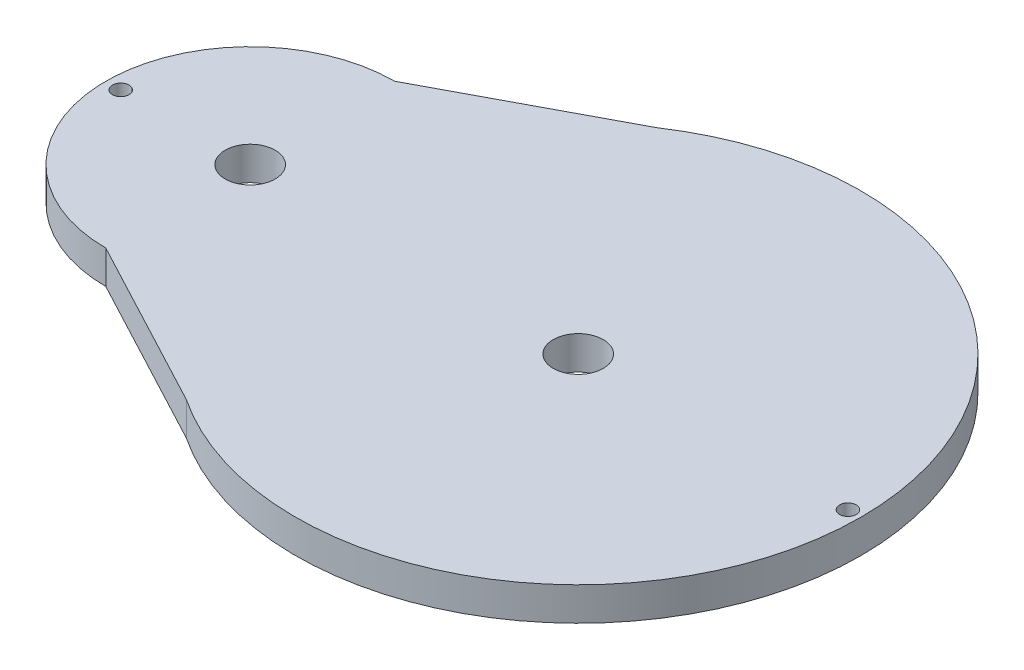
SolidWorks part; units mm, degrees
ref_plane "Front Plane" through (0, 0, 0) normal (0, 0, 1) x (1, 0, 0)
ref_plane "Top Plane" through (0, 0, 0) normal (0, 1, 0) x (1, 0, 0)
ref_plane "Right Plane" through (0, 0, 0) normal (1, 0, 0) x (0, 0, -1)
sketch "Sketch1" plane through (0, 0, 0) normal (0, 1, 0) x (1, 0, 0)
  line L0 (-27.1461, 33.0749) -> (3.7062, 49.4352)
  line L1 (-27.1461, -18.9251) -> (3.7062, -35.2855)
  line L2 (-27.1461, 28.0749) -> (6.7029, 43.7842)
  line L3 (-27.1461, -13.9251) -> (3.7062, -27.3857)
  circle A0 centre (31.9089, 7.0749) radius 44.53
  circle A2 centre (-27.1461, 7.0749) radius 4.5
  circle A3 centre (31.9089, 7.0749) radius 4.5
  circle A4 centre (31.9089, 7.0749) radius 50.89
  arc A5 (-27.1461, -18.9251) -> (-27.1461, 33.0749) centre (-27.1461, 7.0749) cw
  arc A6 (-27.1461, 28.0749) -> (-27.1461, -13.9251) centre (-27.1461, 7.0749) ccw
extrude "Boss-Extrude1" add sketch "Sketch1" along normal blind 6 contours A6 L2 A4 L0 A5 L1 L3 | L2 A6 L3 A4 A2 | L2 A4 L3 A0 | A4 L2 A0 L3 | A0 A3
sketch "Sketch2" plane through (0, 6, 0) normal (0, 1, 0) x (1, 0, 0)
  line L0 (-27.1461, 33.0749) -> (3.7062, 49.4352)
  line L1 (-27.1461, -18.9251) -> (3.7062, -35.2855)
  line L2 (-27.1461, 28.0749) -> (4.8405, 44.5702)
  line L3 (-27.1461, -13.9251) -> (4.8405, -30.4205)
  arc A0 (-27.1461, -18.9251) -> (-27.1461, 33.0749) centre (-27.1461, 7.0749) cw
  arc A1 (-27.1461, 33.0749) -> (-27.1461, -18.9251) centre (-27.1461, 7.0749) ccw construction
  arc A2 (31.9089, 57.9649) -> (31.9089, -43.8151) centre (31.9089, 7.0749) cw
  arc A3 (3.7062, -35.2855) -> (3.7062, 49.4352) centre (31.9089, 7.0749) ccw construction
  arc A4 (-27.1461, 28.0749) -> (-27.1461, -13.9251) centre (-27.1461, 7.0749) ccw
  circle A5 centre (31.9089, 7.0749) radius 46.245
  circle A6 centre (-50.4461, 7.0749) radius 1.5
  circle A7 centre (80.4589, 7.0749) radius 1.5
  point P26 (-48.1461, 7.0749)
  dimension "D1" = 2.3
  dimension "D2" = 48.55
extrude "Cut-Extrude1" cut sketch "Sketch2" against normal blind 10 contours A6 | A7
